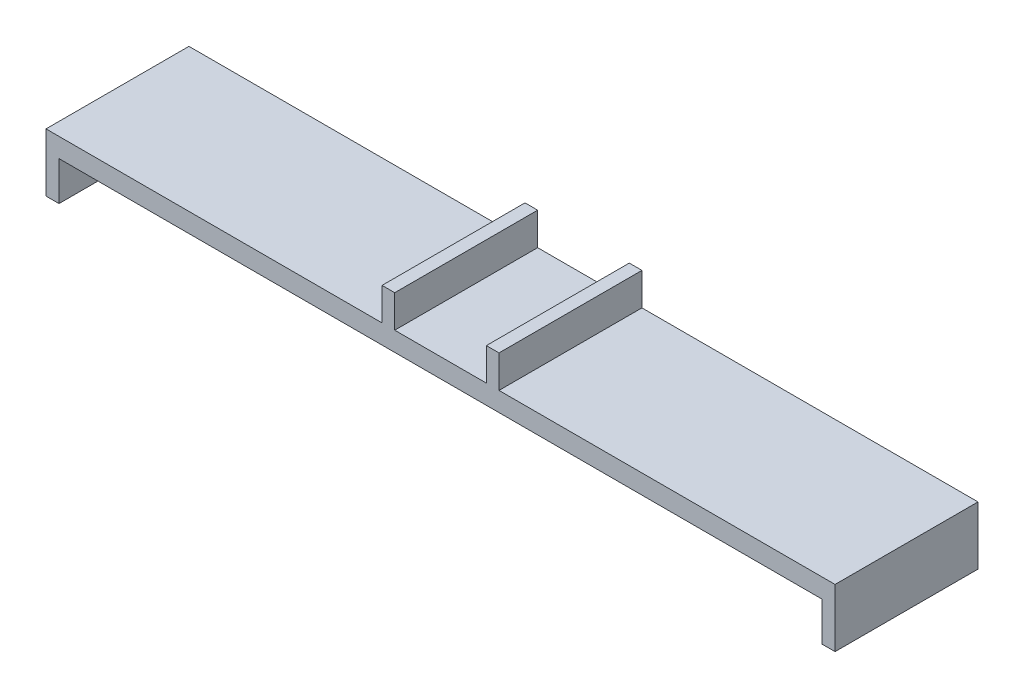
SolidWorks part; units mm, degrees
ref_plane "Front Plane" through (0, 0, 0) normal (0, 0, 1) x (1, 0, 0)
ref_plane "Top Plane" through (0, 0, 0) normal (0, 1, 0) x (1, 0, 0)
ref_plane "Right Plane" through (0, 0, 0) normal (1, 0, 0) x (0, 0, -1)
sketch "Sketch1" plane through (0, 0, 0) normal (0, 0, 1) x (1, 0, 0)
  line L3 (0, 19.6) -> (10, 19.6) construction
  line L4 (20, 19.6) -> (20, 44.8) construction
  line L5 (0, 0) -> (10, 0)
  line L6 (303.6, 0) -> (303.6, 41.1401) construction
  line L9 (0, 0) -> (10, 0)
  line L10 (607.2, 44.8) -> (0, 44.8)
  line L11 (0, 44.8) -> (0, 0)
  line L12 (10, 0) -> (10, 30)
  line L13 (10, 30) -> (597.2, 30)
  line L14 (597.2, 0) -> (597.2, 30)
  line L15 (607.2, 0) -> (597.2, 0)
  line L16 (607.2, 44.8) -> (607.2, 0)
  line L17 (10, 30) -> (597.2, 30)
  point P12 (303.6, 44.8)
  point P15 (303.6, 44.8)
  point P18 (303.6, 30)
  point P19 (303.6, 30)
  dimension "D5" = 30
  dimension "D1" = 19.6
  dimension "D2" = 20
  dimension "D3" = 587.2
  dimension "D4" = 14.8
extrude "Boss-Extrude2" add sketch "Sketch1" along normal blind 110
sketch "Sketch3" plane through (0, 39.6, 0) normal (0, 1, 0) x (1, 0, 0)
  line L0 (338.8557, -110) -> (348.6, -110)
  line L2 (607.2, 0) -> (0, 0) construction
  line L3 (303.6, 0) -> (303.6, -151.4972) construction
  line L16 (348.6, 0) -> (338.8557, 0)
  line L20 (348.6, -110) -> (348.6, 0)
  line L24 (268.3443, -110) -> (258.6, -110)
  line L25 (338.8557, 0) -> (338.8557, -110)
  line L26 (258.6, 0) -> (268.3443, 0)
  line L28 (268.3443, 0) -> (268.3443, -110)
  line L29 (258.6, -110) -> (258.6, 0)
extrude "Boss-Extrude3" add sketch "Sketch3" along normal blind 30.2
